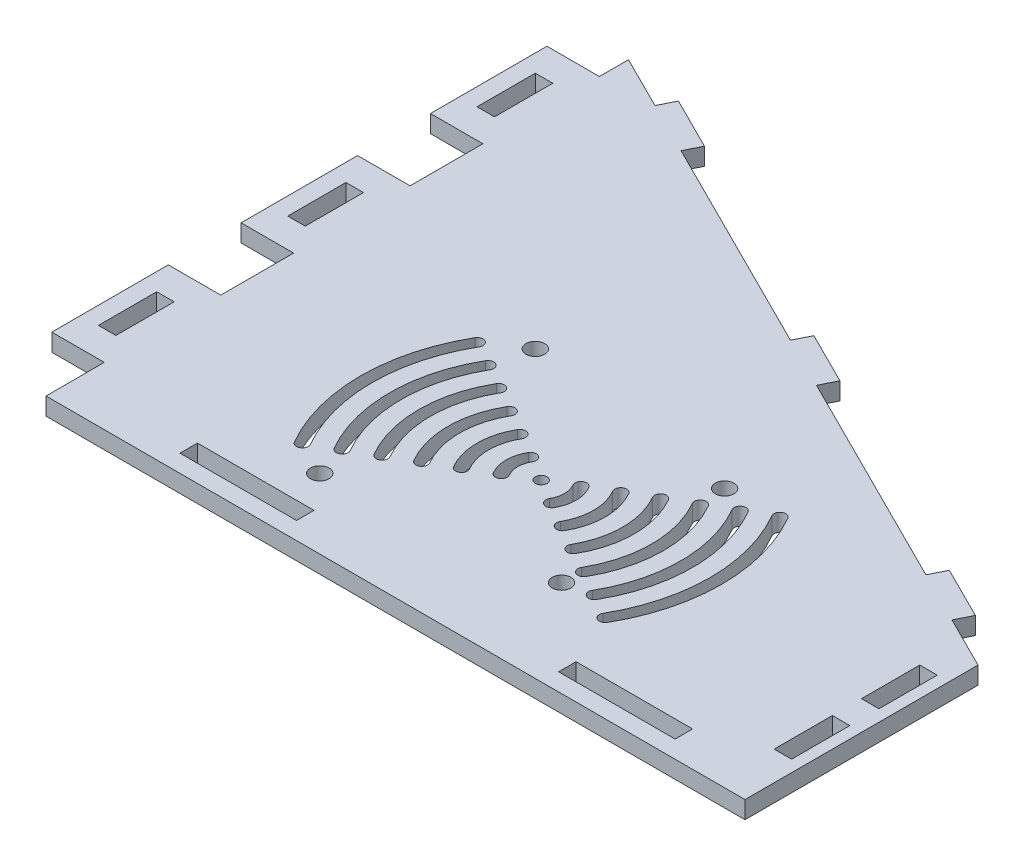
SolidWorks part; units mm, degrees
material "ABS"
ref_plane "Front Plane" through (0, 0, 0) normal (0, 0, 1) x (1, 0, 0)
ref_plane "Top Plane" through (0, 0, 0) normal (0, 1, 0) x (1, 0, 0)
ref_plane "Right Plane" through (0, 0, 0) normal (1, 0, 0) x (0, 0, -1)
sketch "Sketch1" plane through (0, 0, 0) normal (0, 1, 0) x (1, 0, 0)
  line L0 (0, 0) -> (0, 10)
  line L1 (0, 100) -> (9.091, 95.4545)
  line L2 (120, 40) -> (120, 0)
  line L3 (120, 0) -> (0, 0)
  line L4 (9.091, 95.4545) -> (10.4327, 98.1378)
  line L5 (10.4327, 98.1378) -> (19.3769, 93.6656)
  line L6 (19.3769, 93.6656) -> (18.0353, 90.9823)
  line L7 (55.6012, 72.1994) -> (56.9429, 74.8827)
  line L8 (56.9429, 74.8827) -> (65.8872, 70.4105)
  line L9 (65.8872, 70.4105) -> (64.5455, 67.7272)
  line L10 (102.1115, 48.9443) -> (103.4531, 51.6276)
  line L11 (103.4531, 51.6276) -> (112.3974, 47.1554)
  line L12 (112.3974, 47.1554) -> (111.0557, 44.4721)
  line L13 (18.0353, 90.9823) -> (55.6012, 72.1994)
  line L14 (64.5455, 67.7272) -> (102.1115, 48.9443)
  line L15 (111.0557, 44.4721) -> (120, 40)
  line L16 (0, 95) -> (0, 100)
  line L17 (115, 35) -> (118, 35)
  line L18 (115, 35) -> (115, 25)
  line L19 (115, 25) -> (118, 25)
  line L20 (118, 35) -> (118, 25)
  line L21 (115, 20) -> (118, 20)
  line L22 (115, 20) -> (115, 10)
  line L23 (115, 10) -> (118, 10)
  line L24 (118, 20) -> (118, 10)
  line L25 (-9, 95) -> (0, 95)
  line L26 (-9, 95) -> (-9, 75)
  line L27 (-9, 75) -> (0, 75)
  line L29 (-9, 62.5) -> (0, 62.5)
  line L30 (-9, 62.5) -> (-9, 42.5)
  line L31 (-9, 42.5) -> (0, 42.5)
  line L33 (-9, 30) -> (0, 30)
  line L34 (-9, 30) -> (-9, 10)
  line L35 (-9, 10) -> (0, 10)
  line L37 (20, 3) -> (40, 3)
  line L38 (20, 3) -> (20, 6)
  line L39 (20, 6) -> (40, 6)
  line L40 (40, 3) -> (40, 6)
  line L41 (85, 6) -> (105, 6)
  line L42 (85, 6) -> (85, 3)
  line L43 (85, 3) -> (105, 3)
  line L44 (105, 6) -> (105, 3)
  line L45 (0, 62.5) -> (0, 75)
  line L46 (0, 30) -> (0, 42.5)
  line L48 (-6, 90) -> (-3, 90)
  line L49 (-6, 90) -> (-6, 80)
  line L50 (-6, 80) -> (-3, 80)
  line L51 (-3, 90) -> (-3, 80)
  line L52 (-6, 57.5) -> (-3, 57.5)
  line L53 (-6, 57.5) -> (-6, 47.5)
  line L54 (-6, 47.5) -> (-3, 47.5)
  line L55 (-3, 57.5) -> (-3, 47.5)
  line L56 (-6, 25) -> (-3, 25)
  line L57 (-6, 25) -> (-6, 15)
  line L58 (-6, 15) -> (-3, 15)
  line L59 (-3, 25) -> (-3, 15)
  point P13 (65.2163, 69.0689)
  dimension "D1" = 100
  dimension "D2" = 40
  dimension "D3" = 10
  dimension "D4" = 10
  dimension "D5" = 10
  dimension "D6" = 120
  dimension "D7" = 3
  dimension "D8" = 42
  dimension "D9" = 3
  dimension "D10" = 42
  dimension "D11" = 10
  dimension "D12" = 3
  dimension "D13" = 10
  dimension "D14" = 10
  dimension "D15" = 3
  dimension "D16" = 3
  dimension "D17" = 10
  dimension "D18" = 5
  dimension "D19" = 2
  dimension "D20" = 2
  dimension "D21" = 12.5
  dimension "D22" = 9
  dimension "D23" = 3
  dimension "D24" = 20
  dimension "D25" = 20
  dimension "D26" = 20
  dimension "D27" = 10
  dimension "D28" = 10
  dimension "D29" = 12.5
  dimension "D30" = 9
  dimension "D31" = 3
  dimension "D32" = 9
  dimension "D33" = 20
  dimension "D34" = 20
  dimension "D35" = 3
  dimension "D36" = 3
  dimension "D37" = 3
  dimension "D38" = 3
  dimension "D39" = 15
  dimension "D40" = 20
  dimension "D41" = 5
  dimension "D42" = 10
  dimension "D43" = 3
  dimension "D44" = 3
  dimension "D45" = 5
  dimension "D46" = 10
  dimension "D47" = 3
  dimension "D48" = 3
  dimension "D49" = 5
extrude "Boss-Extrude1" add sketch "Sketch1" along normal blind 3
sketch "Sketch2" plane through (0, 0, 0) normal (0, -1, 0) x (1, 0, 0)
  line L0 (24.6891, -12.5) -> (85.3109, -47.5) construction
  line L1 (24.6891, -47.5) -> (85.3109, -12.5) construction
  line L2 (0, 0) -> (120, 0) construction
  line L3 (0, -42.5) -> (0, -30) construction
  line L4 (55, -30) -> (55, -3.2885) construction
  line L5 (0, 0) -> (120, 0) construction
  line L6 (0, -10) -> (0, 0) construction
  circle A0 centre (55, -30) radius 1
  arc A1 (50.6699, -32.5) -> (50.6699, -27.5) centre (55, -30) cw construction
  arc A2 (49.8038, -27) -> (49.8038, -33) centre (55, -30) ccw
  arc A3 (51.5359, -28) -> (51.5359, -32) centre (55, -30) ccw
  arc A4 (51.5359, -28) -> (49.8038, -27) centre (50.6699, -27.5) ccw
  arc A5 (49.8038, -33) -> (51.5359, -32) centre (50.6699, -32.5) ccw
  arc A6 (46.3397, -35) -> (46.3397, -25) centre (55, -30) cw construction
  arc A7 (45.4737, -24.5) -> (45.4737, -35.5) centre (55, -30) ccw
  arc A8 (47.2058, -25.5) -> (47.2058, -34.5) centre (55, -30) ccw
  arc A9 (47.2058, -25.5) -> (45.4737, -24.5) centre (46.3397, -25) ccw
  arc A10 (45.4737, -35.5) -> (47.2058, -34.5) centre (46.3397, -35) ccw
  arc A11 (42.0096, -22.5) -> (42.0096, -37.5) centre (55, -30) ccw construction
  arc A12 (41.1436, -22) -> (41.1436, -38) centre (55, -30) ccw
  arc A13 (42.8756, -23) -> (42.8756, -37) centre (55, -30) ccw
  arc A14 (42.8756, -23) -> (41.1436, -22) centre (42.0096, -22.5) ccw
  arc A15 (41.1436, -38) -> (42.8756, -37) centre (42.0096, -37.5) ccw
  arc A16 (37.6795, -40) -> (37.6795, -20) centre (55, -30) cw construction
  arc A17 (36.8135, -19.5) -> (36.8135, -40.5) centre (55, -30) ccw
  arc A18 (38.5455, -20.5) -> (38.5455, -39.5) centre (55, -30) ccw
  arc A19 (38.5455, -20.5) -> (36.8135, -19.5) centre (37.6795, -20) ccw
  arc A20 (36.8135, -40.5) -> (38.5455, -39.5) centre (37.6795, -40) ccw
  arc A21 (33.3494, -17.5) -> (33.3494, -42.5) centre (55, -30) ccw construction
  arc A22 (32.4833, -17) -> (32.4833, -43) centre (55, -30) ccw
  arc A23 (34.2154, -18) -> (34.2154, -42) centre (55, -30) ccw
  arc A24 (34.2154, -18) -> (32.4833, -17) centre (33.3494, -17.5) ccw
  arc A25 (32.4833, -43) -> (34.2154, -42) centre (33.3494, -42.5) ccw
  arc A26 (29.0192, -15) -> (29.0192, -45) centre (55, -30) ccw construction
  arc A27 (28.1532, -14.5) -> (28.1532, -45.5) centre (55, -30) ccw
  arc A28 (29.8853, -15.5) -> (29.8853, -44.5) centre (55, -30) ccw
  arc A29 (29.8853, -15.5) -> (28.1532, -14.5) centre (29.0192, -15) ccw
  arc A30 (28.1532, -45.5) -> (29.8853, -44.5) centre (29.0192, -45) ccw
  arc A31 (80.9808, -15) -> (80.9808, -45) centre (55, -30) cw construction
  arc A32 (81.8468, -14.5) -> (81.8468, -45.5) centre (55, -30) cw
  arc A33 (80.1147, -15.5) -> (80.1147, -44.5) centre (55, -30) cw
  arc A34 (80.1147, -15.5) -> (81.8468, -14.5) centre (80.9808, -15) cw
  arc A35 (81.8468, -45.5) -> (80.1147, -44.5) centre (80.9808, -45) cw
  arc A36 (76.6506, -17.5) -> (76.6506, -42.5) centre (55, -30) cw construction
  arc A37 (77.5167, -17) -> (77.5167, -43) centre (55, -30) cw
  arc A38 (75.7846, -18) -> (75.7846, -42) centre (55, -30) cw
  arc A39 (75.7846, -18) -> (77.5167, -17) centre (76.6506, -17.5) cw
  arc A40 (77.5167, -43) -> (75.7846, -42) centre (76.6506, -42.5) cw
  arc A41 (72.3205, -40) -> (72.3205, -20) centre (55, -30) ccw construction
  arc A42 (73.1865, -19.5) -> (73.1865, -40.5) centre (55, -30) cw
  arc A43 (71.4545, -20.5) -> (71.4545, -39.5) centre (55, -30) cw
  arc A44 (71.4545, -20.5) -> (73.1865, -19.5) centre (72.3205, -20) cw
  arc A45 (73.1865, -40.5) -> (71.4545, -39.5) centre (72.3205, -40) cw
  arc A46 (67.9904, -22.5) -> (67.9904, -37.5) centre (55, -30) cw construction
  arc A47 (68.8564, -22) -> (68.8564, -38) centre (55, -30) cw
  arc A48 (67.1244, -23) -> (67.1244, -37) centre (55, -30) cw
  arc A49 (67.1244, -23) -> (68.8564, -22) centre (67.9904, -22.5) cw
  arc A50 (68.8564, -38) -> (67.1244, -37) centre (67.9904, -37.5) cw
  arc A51 (63.6603, -35) -> (63.6603, -25) centre (55, -30) ccw construction
  arc A52 (64.5263, -24.5) -> (64.5263, -35.5) centre (55, -30) cw
  arc A53 (62.7942, -25.5) -> (62.7942, -34.5) centre (55, -30) cw
  arc A54 (62.7942, -25.5) -> (64.5263, -24.5) centre (63.6603, -25) cw
  arc A55 (64.5263, -35.5) -> (62.7942, -34.5) centre (63.6603, -35) cw
  arc A56 (59.3301, -32.5) -> (59.3301, -27.5) centre (55, -30) ccw construction
  arc A57 (60.1962, -27) -> (60.1962, -33) centre (55, -30) cw
  arc A58 (58.4641, -28) -> (58.4641, -32) centre (55, -30) cw
  arc A59 (58.4641, -28) -> (60.1962, -27) centre (59.3301, -27.5) cw
  arc A60 (60.1962, -33) -> (58.4641, -32) centre (59.3301, -32.5) cw
  circle A61 centre (35, -49) radius 1.6
  circle A62 centre (72, -44.5) radius 1.6
  circle A63 centre (72, -16.5) radius 1.6
  circle A64 centre (35, -12) radius 1.6
  point P5 (55, -30)
  point P8 (55, -30)
  point P14 (50, -30)
  point P19 (45, -30)
  point P27 (40, -30)
  point P35 (35, -30)
  point P46 (30, -30)
  point P51 (25, -30)
  point P63 (85, -30)
  point P70 (80, -30)
  point P77 (75, -30)
  point P84 (70, -30)
  point P91 (65, -30)
  point P98 (60, -30)
  point P115 (22.2721, -8.1503)
  dimension "D1" = 2
  dimension "D8" = 1
  dimension "D9" = 1
  dimension "D10" = 1
  dimension "D11" = 1
  dimension "D16" = 1
  dimension "D17" = 1
  dimension "D20" = 3.2
  dimension "D21" = 37
  dimension "D22" = 37
  dimension "D2" = 60
  dimension "D3" = 30
  dimension "D4" = 30
  dimension "D5" = 55
  dimension "D6" = 70
  dimension "D7" = 70
  dimension "D12" = 5
  dimension "D13" = 10
  dimension "D14" = 15
  dimension "D15" = 20
  dimension "D18" = 25
  dimension "D19" = 30
  dimension "D23" = 28
  dimension "D24" = 4.5
  dimension "D25" = 37
  dimension "D26" = 12
  dimension "D27" = 35
extrude "Cut-Extrude1" cut sketch "Sketch2" against normal blind 3
